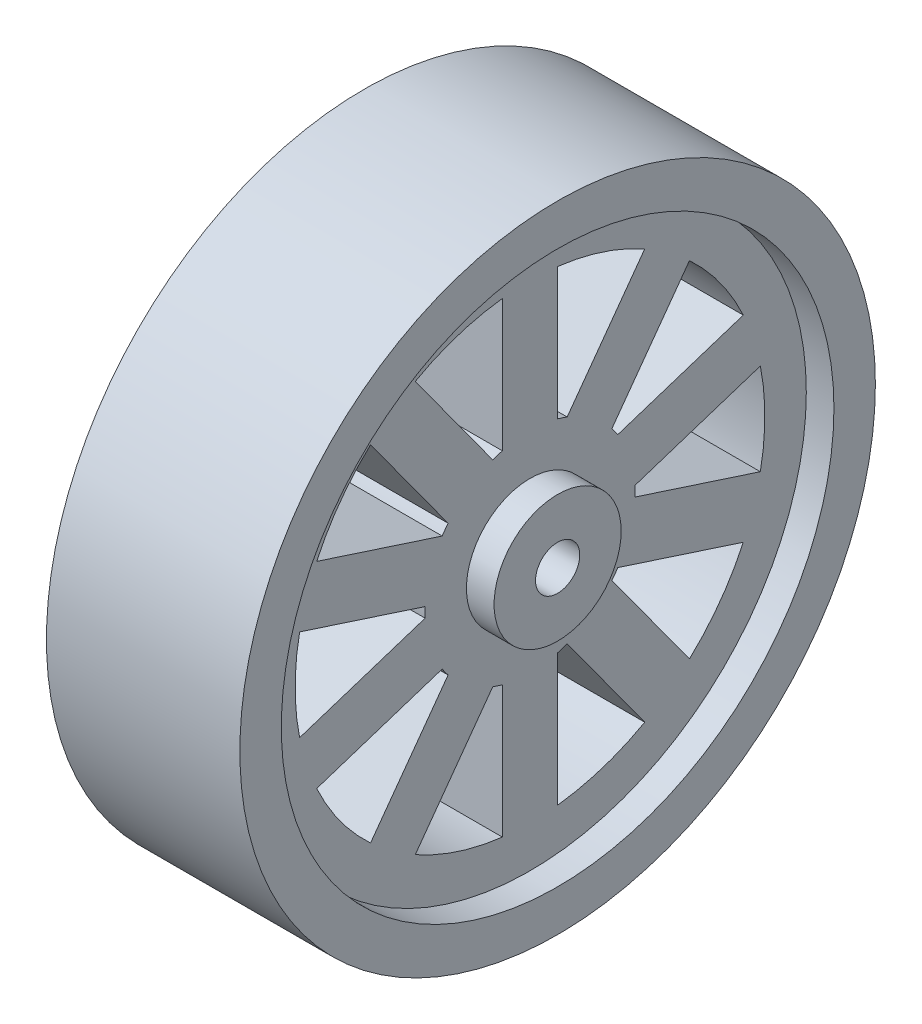
SolidWorks part; units mm, degrees
ref_plane "Front Plane" through (0, 0, 0) normal (0, 0, 1) x (1, 0, 0)
ref_plane "Top Plane" through (0, 0, 0) normal (0, 1, 0) x (1, 0, 0)
ref_plane "Right Plane" through (0, 0, 0) normal (1, 0, 0) x (0, 0, -1)
sketch "Sketch1" plane through (0, 0, 0) normal (1, 0, 0) x (0, 0, -1)
  circle A0 centre (0, 0) radius 2.032
  circle A1 centre (0, 0) radius 29.21
  dimension "D1" = 4.064
  dimension "D2" = 58.42
extrude "Boss-Extrude1" add sketch "Sketch1" along normal mid plane 17.78
sketch "Sketch2" plane through (8.89, 0, 0) normal (1, 0, 0) x (0, 0, -1)
  line L0 (0, -1010.16) -> (0, -9.652) construction
  line L1 (-2.54, 21.4401) -> (-2.54, 9.3118)
  line L2 (2.54, 21.4401) -> (2.54, 9.3118)
  line L3 (14.6571, 15.8524) -> (7.5282, 6.0404)
  line L4 (10.5473, 18.8384) -> (3.4184, 9.0264)
  line L5 (21.1756, 4.2097) -> (9.6409, 0.4618)
  line L6 (19.6058, 9.041) -> (8.0711, 5.2932)
  line L7 (19.6058, -9.041) -> (8.0711, -5.2932)
  line L8 (21.1756, -4.2097) -> (9.6409, -0.4618)
  line L9 (10.5473, -18.8384) -> (3.4184, -9.0264)
  line L10 (14.6571, -15.8524) -> (7.5282, -6.0404)
  line L11 (-2.54, -21.4401) -> (-2.54, -9.3118)
  line L12 (2.54, -21.4401) -> (2.54, -9.3118)
  line L13 (-14.6571, -15.8524) -> (-7.5282, -6.0404)
  line L14 (-10.5473, -18.8384) -> (-3.4184, -9.0264)
  line L15 (-21.1756, -4.2097) -> (-9.6409, -0.4618)
  line L16 (-19.6058, -9.041) -> (-8.0711, -5.2932)
  line L17 (-19.6058, 9.041) -> (-8.0711, 5.2932)
  line L18 (-21.1756, 4.2097) -> (-9.6409, 0.4618)
  line L19 (-10.5473, 18.8384) -> (-3.4184, 9.0264)
  line L20 (-14.6571, 15.8524) -> (-7.5282, 6.0404)
  line L21 (0, 5.08) -> (0, 20.1055) construction
  arc A0 (3.4184, 9.0264) -> (2.54, 9.3118) centre (0, 0) ccw
  circle A1 centre (0, 0) radius 2.032 construction
  arc A2 (10.5473, 18.8384) -> (2.54, 21.4401) centre (0, 0) ccw
  circle A3 centre (0, 0) radius 29.21 construction
  arc A4 (-2.54, 21.4401) -> (-10.5473, 18.8384) centre (0, 0) ccw
  arc A5 (-2.54, 9.3118) -> (-3.4184, 9.0264) centre (0, 0) ccw
  arc A6 (8.0711, 5.2932) -> (7.5282, 6.0404) centre (0, 0) ccw
  arc A7 (19.6058, 9.041) -> (14.6571, 15.8524) centre (0, 0) ccw
  arc A8 (9.6409, -0.4618) -> (9.6409, 0.4618) centre (0, 0) ccw
  arc A9 (21.1756, -4.2097) -> (21.1756, 4.2097) centre (0, 0) ccw
  arc A10 (7.5282, -6.0404) -> (8.0711, -5.2932) centre (0, 0) ccw
  arc A11 (14.6571, -15.8524) -> (19.6058, -9.041) centre (0, 0) ccw
  arc A12 (-14.6571, 15.8524) -> (-19.6058, 9.041) centre (0, 0) ccw
  arc A13 (-7.5282, 6.0404) -> (-8.0711, 5.2932) centre (0, 0) ccw
  arc A14 (-9.6409, 0.4618) -> (-9.6409, -0.4618) centre (0, 0) ccw
  arc A15 (-21.1756, 4.2097) -> (-21.1756, -4.2097) centre (0, 0) ccw
  arc A16 (-19.6058, -9.041) -> (-14.6571, -15.8524) centre (0, 0) ccw
  arc A17 (-8.0711, -5.2932) -> (-7.5282, -6.0404) centre (0, 0) ccw
  arc A18 (-3.4184, -9.0264) -> (-2.54, -9.3118) centre (0, 0) ccw
  arc A19 (-10.5473, -18.8384) -> (-2.54, -21.4401) centre (0, 0) ccw
  arc A20 (2.54, -9.3118) -> (3.4184, -9.0264) centre (0, 0) ccw
  arc A21 (2.54, -21.4401) -> (10.5473, -18.8384) centre (0, 0) ccw
  point P53 (0, 0)
  dimension "D1" = 7.62
  dimension "D2" = 7.62
  dimension "D3" = 5.08
  dimension "D4" = 10
extrude "Cut-Extrude1" cut sketch "Sketch2" against normal through all both and the other way through all
sketch "Sketch3" plane through (8.89, 0, 0) normal (1, 0, 0) x (0, 0, -1)
  circle A0 centre (0, 0) radius 5.842
  circle A1 centre (0, 0) radius 25.4
  circle A2 centre (0, 0) radius 29.21 construction
  circle A3 centre (0, 0) radius 2.032 construction
  dimension "D1" = 3.81
  dimension "D2" = 3.81
extrude "Cut-Extrude2" cut sketch "Sketch3" against normal blind 2.54
